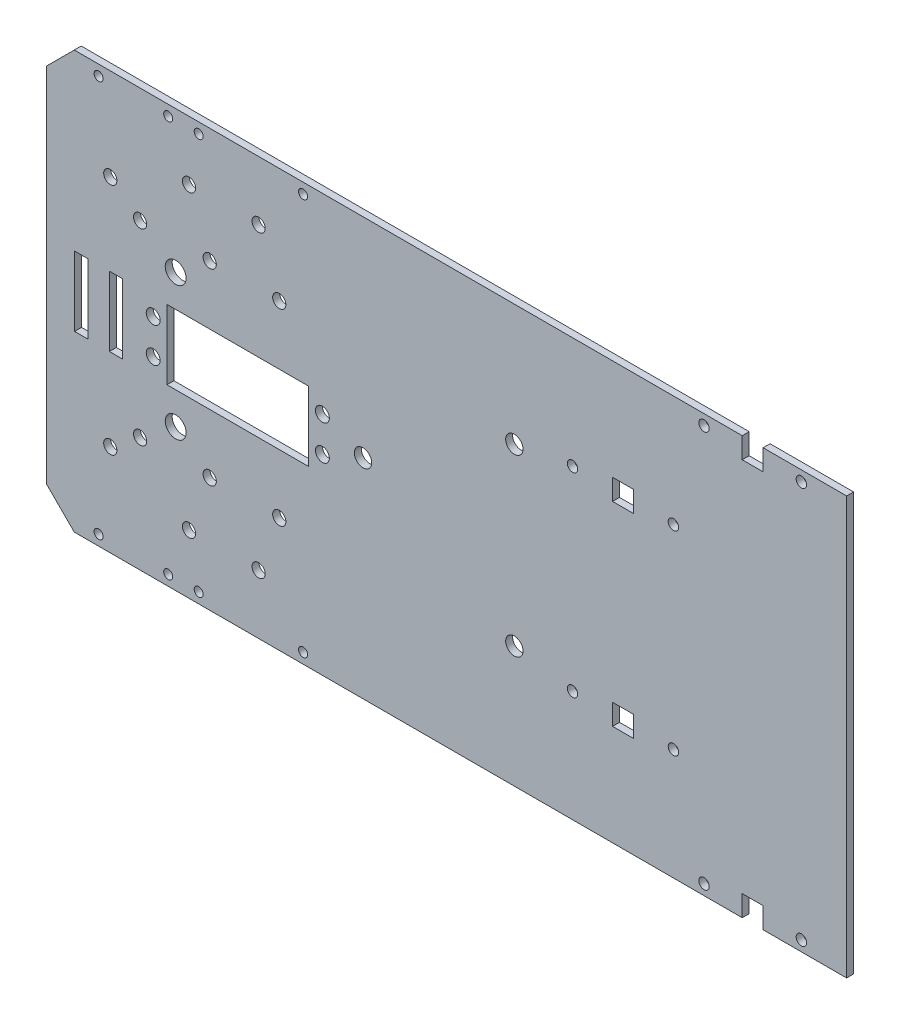
SolidWorks part; units mm, degrees
ref_plane "前视基准面" through (0, 0, 0) normal (0, 0, 1) x (1, 0, 0)
ref_plane "上视基准面" through (0, 0, 0) normal (0, 1, 0) x (1, 0, 0)
ref_plane "右视基准面" through (0, 0, 0) normal (1, 0, 0) x (0, 0, -1)
sketch "草图5" plane through (0, 0, 0) normal (0, 0, 1) x (1, 0, 0)
  line L1 (-115, 60) -> (115, 60)
  line L2 (-115, 60) -> (-115, -60)
  line L3 (-115, -60) -> (115, -60)
  line L4 (115, 60) -> (115, -60)
  line L5 (-115, 60) -> (115, -60) construction
  line L6 (-115, -60) -> (115, 60) construction
  point P0 (0, 0)
  dimension "D1" = 120
  dimension "D2" = 230
extrude "凸台-拉伸2" add sketch "草图5" along normal blind 2
sketch "草图6" plane through (0, 0, 2) normal (0, 0, 1) x (1, 0, 0)
  line L0 (-115, 60) -> (-115, -60) construction
  line L1 (115, -60) -> (115, 60) construction
  line L2 (115, 0) -> (-115, 0) construction
  circle A0 centre (-24, 0) radius 2.5
  circle A1 centre (19.5, 25.1147) radius 2.5
  circle A2 centre (19.5, -25.1147) radius 2.5
  point P15 (5, 0)
  dimension "D2" = 29
  dimension "D3" = 110
  dimension "D1" = 3
extrude "切除-拉伸3" cut sketch "草图6" against normal through all
sketch "草图7" plane through (0, 0, 2) normal (0, 0, 1) x (1, 0, 0)
  line L0 (-115, 0) -> (115, 0) construction
  line L1 (-115, 60) -> (-115, -60) construction
  line L2 (115, -60) -> (115, 60) construction
  line L3 (115, 60) -> (-115, 60) construction
  line L4 (85, 60) -> (91, 60)
  line L5 (85, 60) -> (85, 54)
  line L6 (85, 54) -> (91, 54)
  line L7 (91, 60) -> (91, 54)
  line L8 (88, 60) -> (88, 54) construction
  line L9 (52.9399, 57) -> (85, 57) construction
  line L10 (85, 57) -> (91, 57) construction
  line L11 (91, 57) -> (94.1573, 57) construction
  line L12 (85, -60) -> (85, -54)
  line L13 (85, -54) -> (91, -54)
  line L14 (91, -60) -> (91, -54)
  line L15 (85, -60) -> (91, -60)
  circle A0 centre (74, 57) radius 1.5
  circle A1 centre (102, 57) radius 1.5
  circle A2 centre (102, -57) radius 1.5
  circle A3 centre (74, -57) radius 1.5
  dimension "D4" = 28
  dimension "D5" = 3
  dimension "D1" = 6
  dimension "D2" = 6
  dimension "D3" = 30
extrude "切除-拉伸4" cut sketch "草图7" against normal through all
sketch "草图8" plane through (0, 0, 2) normal (0, 0, 1) x (1, 0, 0)
  line L0 (-115, 0) -> (115, 0) construction
  line L1 (-115, 60) -> (-115, -60) construction
  line L2 (115, -60) -> (115, 60) construction
  line L3 (47.72, 28) -> (53.72, 28) construction
  line L4 (47.72, 31) -> (53.72, 31)
  line L5 (47.72, 31) -> (47.72, 25)
  line L6 (47.72, 25) -> (53.72, 25)
  line L7 (53.72, 31) -> (53.72, 25)
  line L8 (50.72, 31) -> (50.72, 25) construction
  line L9 (53.72, -31) -> (53.72, -25)
  line L10 (47.72, -25) -> (53.72, -25)
  line L11 (47.72, -31) -> (47.72, -25)
  line L12 (47.72, -31) -> (53.72, -31)
  line L13 (36.22, 28) -> (47.72, 28) construction
  line L14 (85, 60) -> (85, 54) construction
  circle A0 centre (36.22, 28) radius 1.5
  circle A1 centre (65.22, 28) radius 1.5
  circle A2 centre (65.22, -28) radius 1.5
  circle A3 centre (36.22, -28) radius 1.5
  dimension "D1" = 29
  dimension "D2" = 56
  dimension "D6" = 3
  dimension "D3" = 6
  dimension "D4" = 6
  dimension "D5" = 37.28
extrude "切除-拉伸5" cut sketch "草图8" against normal through all
sketch "草图9" plane through (0, 0, 2) normal (0, 0, 1) x (1, 0, 0)
  line L0 (-115, 0) -> (115, 0) construction
  line L1 (-115, 60) -> (-115, -60) construction
  line L2 (115, -60) -> (115, 60) construction
  line L3 (-60, -10) -> (-60, 10) construction
  line L4 (-80.35, 10) -> (-39.65, 10)
  line L5 (-80.35, 10) -> (-80.35, -10)
  line L6 (-80.35, -10) -> (-39.65, -10)
  line L7 (-39.65, 10) -> (-39.65, -10)
  line L8 (-80.35, 10) -> (-39.65, -10) construction
  line L9 (-80.35, -10) -> (-39.65, 10) construction
  circle A0 centre (-84.315, 5) radius 2
  circle A1 centre (-84.315, -5) radius 2
  circle A2 centre (-35.685, -5) radius 2
  circle A3 centre (-35.685, 5) radius 2
  point P6 (-60, 0)
  dimension "D4" = 4
  dimension "D5" = 10
  dimension "D6" = 48.63
  dimension "D1" = 40.7
  dimension "D2" = 20
  dimension "D3" = 55
extrude "切除-拉伸6" cut sketch "草图9" against normal through all
sketch "草图10" plane through (0, 0, 2) normal (0, 0, 1) x (1, 0, 0)
  line L0 (-115, 0) -> (115, 0) construction
  line L1 (-115, 60) -> (-115, -60) construction
  line L2 (115, -60) -> (115, 60) construction
  line L3 (85, 60) -> (-115, 60) construction
  line L4 (-71.2274, 57) -> (-41.2274, 57) construction
  circle A0 centre (-41.2274, 57) radius 1.3
  circle A1 centre (-41.2274, -57) radius 1.3
  circle A2 centre (-71.2274, 57) radius 1.3
  circle A3 centre (-71.2274, -57) radius 1.3
  dimension "D1" = 3
  dimension "D2" = 30
extrude "切除-拉伸7" cut sketch "草图10" against normal through all
sketch "草图11" plane through (0, 0, 2) normal (0, 0, 1) x (1, 0, 0)
  line L0 (-115, 0) -> (115, 0) construction
  line L1 (-115, 60) -> (-115, -60) construction
  line L2 (115, -60) -> (115, 60) construction
  line L3 (85, 60) -> (-115, 60) construction
  line L4 (-100, 57) -> (-80, 57) construction
  circle A0 centre (-100, 57) radius 1.3
  circle A1 centre (-80, 57) radius 1.3
  circle A2 centre (-80, -57) radius 1.3
  circle A3 centre (-100, -57) radius 1.3
  dimension "D1" = 2.6
  dimension "D2" = 2.6
  dimension "D3" = 15
  dimension "D4" = 3
  dimension "D5" = 20
extrude "切除-拉伸8" cut sketch "草图11" against normal through all
sketch "草图12" plane through (0, 0, 2) normal (0, 0, 1) x (1, 0, 0)
  line L0 (-115, 0) -> (115, 0) construction
  line L1 (-115, 60) -> (-115, -60) construction
  line L2 (115, -60) -> (115, 60) construction
  line L3 (-111.2276, 27) -> (-18.3608, 27) construction
  line L4 (-111.2276, 43) -> (-18.3608, 43) construction
  circle A0 centre (-48.0739, 27) radius 1.9
  circle A1 centre (-54.0141, -43) radius 1.9
  circle A2 centre (-68.0739, 27) radius 1.9
  circle A3 centre (-74.0141, 43) radius 1.9
  circle A4 centre (-88.0739, 27) radius 1.9
  circle A5 centre (-54.0141, 43) radius 1.9
  circle A6 centre (-88.0739, -27) radius 1.9
  circle A7 centre (-74.0141, -43) radius 1.9
  circle A8 centre (-68.0739, -27) radius 1.9
  circle A9 centre (-48.0739, -27) radius 1.9
  point P9 (-45.7291, 26.8567)
  point P10 (-50.8877, 26.3877)
  point P22 (-56.8279, 40.9256)
  point P23 (-54.0141, 42.6451)
  point P24 (-71.2094, 26.8567)
  point P25 (-48.0739, 27.1693)
  dimension "D1" = 3.8
  dimension "D2" = 20
  dimension "D3" = 20
  dimension "D4" = 20
  dimension "D5" = 27
  dimension "D6" = 43
extrude "切除-拉伸9" cut sketch "草图12" against normal through all
sketch "草图13" plane through (0, 0, 2) normal (0, 0, 1) x (1, 0, 0)
  line L0 (-115, 0) -> (115, 0) construction
  line L1 (-115, 60) -> (-115, -60) construction
  line L2 (115, -60) -> (115, 60) construction
  line L4 (-96.9, 10) -> (-93.1, 10)
  line L5 (-96.9, 10) -> (-96.9, -10)
  line L6 (-96.9, -10) -> (-93.1, -10)
  line L7 (-93.1, 10) -> (-93.1, -10)
  line L8 (-96.9, 10) -> (-93.1, -10) construction
  line L9 (-96.9, -10) -> (-93.1, 10) construction
  line L10 (-106.9, 10) -> (-103.1, 10)
  line L11 (-106.9, 10) -> (-106.9, -10)
  line L12 (-106.9, -10) -> (-103.1, -10)
  line L13 (-103.1, 10) -> (-103.1, -10)
  line L14 (-106.9, 10) -> (-103.1, -10) construction
  line L15 (-106.9, -10) -> (-103.1, 10) construction
  point P6 (-95, 0)
  point P15 (-105, 0)
  dimension "D1" = 3.8
  dimension "D2" = 20
  dimension "D3" = 20
  dimension "D4" = 3.8
  dimension "D5" = 20
  dimension "D6" = 10
extrude "切除-拉伸10" cut sketch "草图13" against normal through all
sketch "草图14" plane through (0, 0, 2) normal (0, 0, 1) x (1, 0, 0)
  line L0 (-115, 0) -> (115, 0) construction
  line L1 (-115, 60) -> (-115, -60) construction
  line L2 (115, -60) -> (115, 60) construction
  circle A0 centre (-96.6449, 33.5896) radius 1.9
  circle A1 centre (-96.6449, -33.5896) radius 1.9
  point P6 (-96.5653, 37.5498)
  point P7 (-95.7135, 42.0522)
  point P8 (-96.5653, 41.2004)
  point P11 (-96.6449, 33.5896)
extrude "切除-拉伸11" cut sketch "草图14" against normal through all
sketch "草图17" plane through (0, 0, 2) normal (0, 0, 1) x (1, 0, 0)
  line L0 (-115, 0) -> (115, 0) construction
  line L1 (-115, 60) -> (-115, -60) construction
  line L2 (115, -60) -> (115, 60) construction
  circle A0 centre (-77.8553, 19.2384) radius 3
  circle A1 centre (-77.8553, -19.2384) radius 3
  point P8 (-77.8553, 19.2384)
extrude "切除-拉伸12" cut sketch "草图17" against normal through all
chamfer "倒角1" distance 8 angle 45 2 edges at (-115, -60, 1) (-115, 60, 1)
